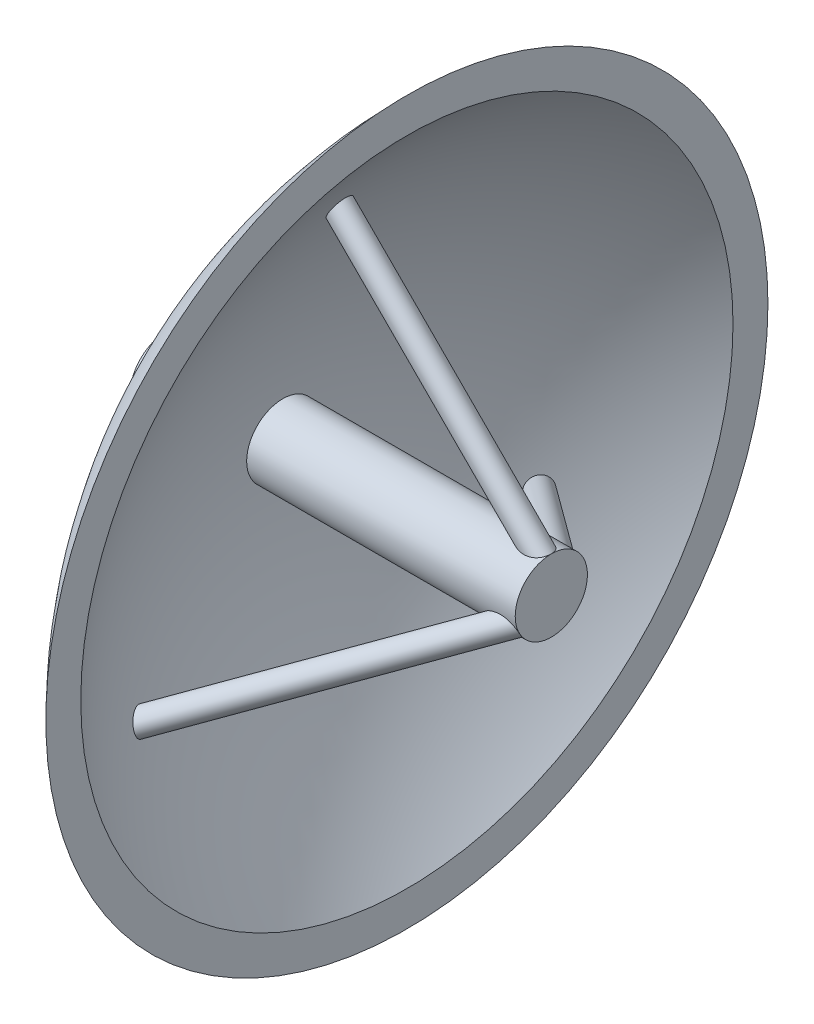
SolidWorks part; units mm, degrees
ref_plane "Front Plane" through (0, 0, 0) normal (0, 0, 1) x (1, 0, 0)
ref_plane "Top Plane" through (0, 0, 0) normal (0, 1, 0) x (1, 0, 0)
ref_plane "Right Plane" through (0, 0, 0) normal (1, 0, 0) x (0, 0, -1)
sketch "Sketch1" plane through (0, 0, 0) normal (0, 1, 0) x (1, 0, 0)
  line L0 (-750, 0) -> (252.9585, 0) construction
  line L1 (-750, 750) -> (-750, 677.4467)
  line L2 (-1060.6602, 0) -> (-1010.6602, 0)
  line L3 (-1110.594, 0) -> (-1010.6602, 0) construction
  arc A0 (-750, 750) -> (-1060.6602, 0) centre (0, 0) ccw
  arc A1 (-750, 677.4467) -> (-1010.6602, 0) centre (0, 0) ccw
  dimension "D2" = 50
  dimension "D3" = 1060.6602
  dimension "D1" = 750
revolve "Revolve1" add sketch "Sketch1" angle 360 about L3
sketch "Sketch2" plane through (-750, 0, 0) normal (1, 0, 0) x (0, 0, -1)
  circle A0 centre (0, 0) radius 75
  dimension "D1" = 150
extrude "Boss-Extrude1" add sketch "Sketch2" against normal blind 500 and the other way blind 300
sketch "Sketch3" plane through (-1250, 0, 0) normal (-1, 0, 0) x (0, 0, 1)
  point P0 (0, 0)
sketch "Sketch5" plane through (0, 0, 0) normal (0, 0, 1) x (1, 0, 0)
  line L0 (-450, 75) -> (-881.0523, 506.0523)
  line L1 (-450, 75) -> (-1007.8735, 75) construction
  line L2 (-450, 75) -> (-467.9605, 57.0395)
  line L3 (-467.9605, 57.0395) -> (-899.0128, 488.0918)
  line L4 (-899.0128, 488.0918) -> (-881.0523, 506.0523)
  dimension "D2" = 609.6
  dimension "D1" = 45
  dimension "D3" = 25.4
revolve "Revolve2" add sketch "Sketch5" angle 360 about L3
pattern_circular "CirPattern1" count 3 over 360 about axis through (-450, 0, 0) along (1, 0, 0) of "Revolve2"
